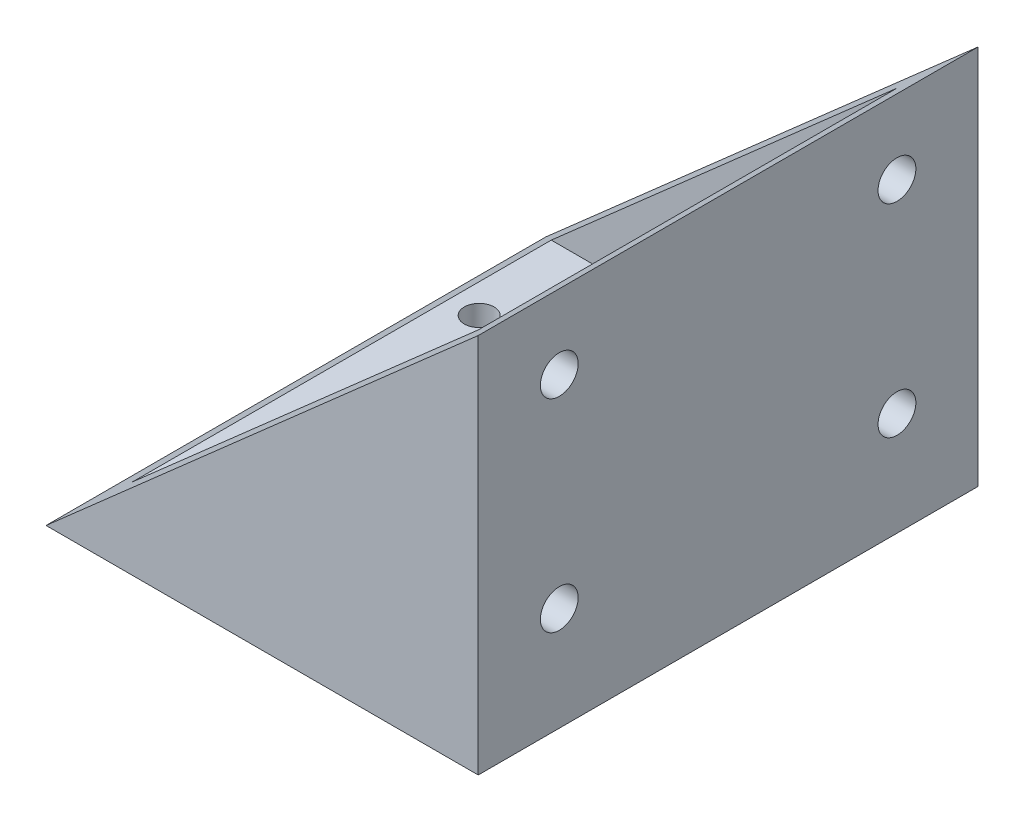
SolidWorks part; units mm, degrees
ref_plane "正面" through (0, 0, 0) normal (0, 0, 1) x (1, 0, 0)
ref_plane "平面" through (0, 0, 0) normal (0, 1, 0) x (1, 0, 0)
ref_plane "右側面" through (0, 0, 0) normal (1, 0, 0) x (0, 0, -1)
sketch "ｽｹｯﾁ1" plane through (0, 0, 0) normal (0, 0, 1) x (1, 0, 0)
  line L0 (0, 0) -> (32, 0)
  line L1 (32, 0) -> (32, 28.1797)
  line L2 (32, 28.1797) -> (0, 0)
  dimension "D1" = 32
extrude "ﾎﾞｽ - 押し出し1" add sketch "ｽｹｯﾁ1" along normal blind 37
shell "ｼｪﾙ1" thickness 3
sketch "ｽｹｯﾁ2" plane through (0, 0, 0) normal (0, -1, 0) x (1, 0, 0)
  line L0 (32, 37) -> (32, 0) construction
  line L1 (26.57, 31.5) -> (5.57, 31.5) construction
  line L2 (26.57, 31.5) -> (26.57, 10.5) construction
  line L3 (26.57, 10.5) -> (5.57, 10.5) construction
  line L4 (5.57, 31.5) -> (5.57, 10.5) construction
  line L5 (26.57, 31.5) -> (5.57, 10.5) construction
  line L6 (26.57, 10.5) -> (5.57, 31.5) construction
  line L8 (32, 37) -> (0, 37) construction
  circle A0 centre (26.57, 10.5) radius 1.1
  circle A1 centre (5.57, 10.5) radius 1.1
  circle A2 centre (5.57, 31.5) radius 1.1
  circle A3 centre (26.57, 31.5) radius 1.1
  point P0 (16.07, 21)
  point P9 (13.5364, 15.7814)
  point P10 (9.3219, 15.4966)
  point P18 (-7.555, 31.5)
  dimension "D1" = 2.2
  dimension "D2" = 21
  dimension "D3" = 21
  dimension "D4" = 5.43
  dimension "D5" = 5.5
extrude "ｶｯﾄ - 押し出し1" cut sketch "ｽｹｯﾁ2" against normal blind 30
sketch "ｽｹｯﾁ3" plane through (0, 0, 0) normal (0, -1, 0) x (1, 0, 0)
  circle A0 centre (16.07, 10.5) radius 6.5
  circle A2 centre (26.57, 31.5) radius 1.1
  circle A3 centre (26.57, 31.5) radius 1.1
  circle A4 centre (5.57, 31.5) radius 1.1
  circle A5 centre (5.57, 31.5) radius 1.1
  circle A6 centre (5.57, 10.5) radius 1.1
  circle A7 centre (5.57, 10.5) radius 1.1
  circle A8 centre (26.57, 10.5) radius 1.1
  circle A9 centre (26.57, 10.5) radius 1.1
  point P2 (0, 0)
  point P3 (13.9902, 4.9966)
  dimension "D5" = 13
  dimension "D6" = 10.5
  dimension "D2" = 0
  dimension "D3" = 0
  dimension "D4" = 0
extrude "ｶｯﾄ - 押し出し2" cut sketch "ｽｹｯﾁ3" against normal blind 5 contours A0
sketch "ｽｹｯﾁ4" plane through (32, 0, 0) normal (1, 0, 0) x (0, 0, -1)
  line L0 (-37, 28.1797) -> (0, 28.1797) construction
  line L1 (-6, 22.6797) -> (-31, 22.6797) construction
  line L2 (-6, 22.6797) -> (-6, 7.6797) construction
  line L3 (-6, 7.6797) -> (-31, 7.6797) construction
  line L4 (-31, 22.6797) -> (-31, 7.6797) construction
  line L5 (-6, 22.6797) -> (-31, 7.6797) construction
  line L6 (-6, 7.6797) -> (-31, 22.6797) construction
  line L7 (-37, 0) -> (0, 0) construction
  circle A0 centre (-6, 22.6797) radius 1.4
  circle A1 centre (-31, 22.6797) radius 1.4
  circle A2 centre (-31, 7.6797) radius 1.4
  circle A3 centre (-6, 7.6797) radius 1.4
  point P0 (-18.5, 15.1797)
  point P13 (-19.7419, 10.5613)
  point P14 (-18.5, 0)
  dimension "D1" = 2.8
  dimension "D2" = 25
  dimension "D3" = 15
  dimension "D4" = 13
extrude "ｶｯﾄ - 押し出し3" cut sketch "ｽｹｯﾁ4" against normal blind 5
equation "\"D4@ｽｹｯﾁ2\"=2.43+3"
equation "\"D6@ｽｹｯﾁ3\"=21/2"
